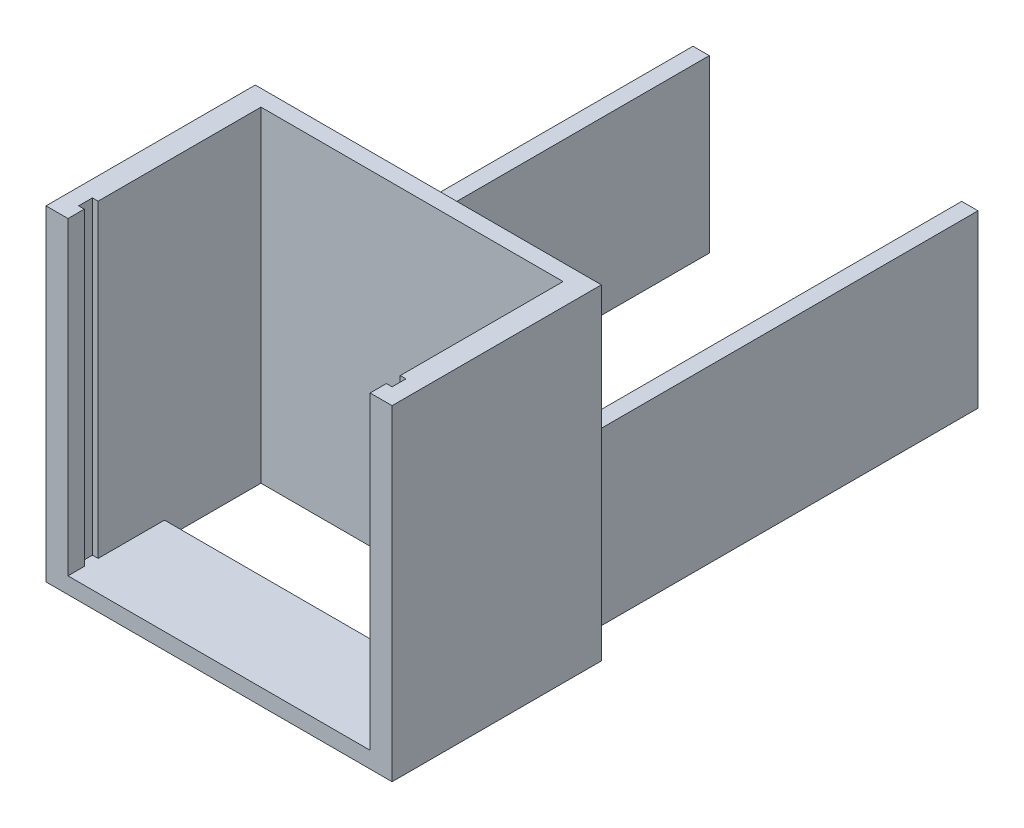
SolidWorks part; units mm, degrees
ref_plane "Front Plane" through (0, 0, 0) normal (0, 0, 1) x (1, 0, 0)
ref_plane "Top Plane" through (0, 0, 0) normal (0, 1, 0) x (1, 0, 0)
ref_plane "Right Plane" through (0, 0, 0) normal (1, 0, 0) x (0, 0, -1)
sketch "Sketch1" plane through (0, 0, 0) normal (0, 1, 0) x (1, 0, 0)
  line L5 (-62.899, -24.3935) -> (-24.399, -24.3935)
  line L6 (-62.899, -24.3935) -> (-62.899, -26.0935)
  line L7 (-62.899, -26.0935) -> (-24.399, -26.0935)
  line L8 (-24.399, -24.3935) -> (-24.399, -26.0935)
  line L9 (-62.199, -22.3935) -> (-25.099, -22.3935)
  line L10 (-62.199, -22.3935) -> (-62.199, -28.0935)
  line L11 (-62.199, -28.0935) -> (-25.099, -28.0935)
  line L12 (-25.099, -22.3935) -> (-25.099, -28.0935)
  line L13 (-64.899, -22.3935) -> (-22.399, -22.3935)
  line L14 (-64.899, -22.3935) -> (-64.899, -28.0935)
  line L15 (-64.899, -28.0935) -> (-22.399, -28.0935)
  line L16 (-22.399, -22.3935) -> (-22.399, -28.0935)
  point P8 (-24.399, -25.2435)
  dimension "D1" = 38.5
  dimension "D2" = 1.7
  dimension "D3" = 2
  dimension "D4" = 2
  dimension "D5" = 0.7
  dimension "D6" = 0.7
  dimension "D7" = 2
  dimension "D8" = 2
  dimension "D9" = 2
  dimension "D10" = 2
extrude "Boss-Extrude1" add sketch "Sketch1" along normal blind 38 contours L14 L15 L10 L7 L6 L5 L13 | L16 L13 L12 L5 L8 L7 L15
sketch "Sketch2" plane through (0, 0, 0) normal (0, 1, 0) x (1, 0, 0)
  line L1 (-64.899, -28.0935) -> (-22.399, -28.0935)
  line L2 (-64.899, -28.0935) -> (-64.899, -22.3935)
  line L3 (-64.899, -22.3935) -> (-22.399, -22.3935)
  line L4 (-22.399, -28.0935) -> (-22.399, -22.3935)
  dimension "D1" = 42.5
  dimension "D2" = 5.7
extrude "Boss-Extrude2" add sketch "Sketch2" against normal blind 2
sketch "Sketch3" plane through (0, 0, 22.3935) normal (0, 0, -1) x (-1, 0, 0)
  line L1 (22.399, 38) -> (64.899, 38)
  line L2 (22.399, 38) -> (22.399, -2)
  line L3 (22.399, -2) -> (64.899, -2)
  line L4 (64.899, 38) -> (64.899, -2)
  line L5 (25.099, 0) -> (62.199, 0)
  line L6 (25.099, 0) -> (25.099, 38)
  line L7 (25.099, 38) -> (62.199, 38)
  line L8 (62.199, 0) -> (62.199, 38)
  line M6 (62.199, 38) -> (62.199, 0)
  line M7 (62.199, 0) -> (25.099, 0)
  line M8 (25.099, 0) -> (25.099, 38)
  line M9 (25.099, 38) -> (22.399, 38)
  line M10 (22.399, 38) -> (22.399, -2)
  line M11 (22.399, -2) -> (64.899, -2)
  line M12 (64.899, -2) -> (64.899, 38)
  line M13 (64.899, 38) -> (62.199, 38)
  dimension "D1" = 42.5
  dimension "D2" = 40
  dimension "D3" = 38
  dimension "D4" = 37.1
extrude "Boss-Extrude3" add sketch "Sketch3" along normal blind 18 contours M13 M6 M7 M8 M9 M10 M11 M12
sketch "Sketch4" plane through (0, 0, 4.3935) normal (0, 0, -1) x (-1, 0, 0)
  line L1 (22.399, 38) -> (64.899, 38)
  line L2 (22.399, 38) -> (22.399, -2)
  line L3 (22.399, -2) -> (64.899, -2)
  line L4 (64.899, 38) -> (64.899, -2)
extrude "Boss-Extrude4" add sketch "Sketch4" along normal blind 2
sketch "Sketch5" plane through (0, 0, 0) normal (0, 1, 0) x (1, 0, 0)
  line L0 (-62.199, -16.2435) -> (-25.099, -16.2435)
  line L1 (-62.199, -4.3935) -> (-25.099, -4.3935)
  line L2 (-62.199, -4.3935) -> (-62.199, -28.0935)
  line L3 (-62.199, -28.0935) -> (-25.099, -28.0935)
  line L4 (-25.099, -4.3935) -> (-25.099, -28.0935)
  line M5 (-25.099, -24.3935) -> (-25.099, -4.3935)
  line M6 (-25.099, -4.3935) -> (-62.199, -4.3935)
  line M7 (-62.199, -4.3935) -> (-62.199, -24.3935)
  dimension "D1" = 37.1
  dimension "D2" = 23.7
  dimension "D3" = 11.85
extrude "Cut-Extrude1" cut sketch "Sketch5" against normal through all contours L0 M7 M5 M6
sketch "Sketch6" plane through (0, 0, 2.3935) normal (0, 0, -1) x (-1, 0, 0)
  line L1 (64.899, 38) -> (22.399, 38)
  line L2 (64.899, 38) -> (64.899, -2)
  line L3 (64.899, -2) -> (22.399, -2)
  line L4 (22.399, 38) -> (22.399, -2)
  line L17 (26.149, 19) -> (28.149, 19)
  line L18 (26.149, 19) -> (26.149, -2)
  line L19 (26.149, -2) -> (28.149, -2)
  line L20 (28.149, 19) -> (28.149, -2)
  line L21 (59.149, 19) -> (61.149, 19)
  line L22 (59.149, 19) -> (59.149, -2)
  line L23 (59.149, -2) -> (61.149, -2)
  line L24 (61.149, 19) -> (61.149, -2)
  dimension "D3" = 2
  dimension "D4" = 2
  dimension "D1" = 19
  dimension "D2" = 19
  dimension "D5" = 31
  dimension "D6" = 3.75
  dimension "D7" = 42.5
extrude "Boss-Extrude6" add sketch "Sketch6" along normal blind 50 contours L20 L17 L18 L3 | L24 L21 L22 L3
equation "\"camera side length\"= 38"
equation "\"camera module panel thickness\"= 1.7"
equation "\"tolerance\"= 0.5"
equation "\"D1@Sketch1\"=\"camera side length\"+\"tolerance\""
equation "\"D2@Sketch1\"=\"camera module panel thickness\""
equation "\"camera module side clearance\"= 0.7"
equation "\"camera mount thickness\"= 2"
equation "\"D3@Sketch1\"=\"camera mount thickness\""
equation "\"D4@Sketch1\"=\"camera mount thickness\""
equation "\"D5@Sketch1\"=\"camera module side clearance\""
equation "\"D6@Sketch1\"=\"camera module side clearance\""
equation "\"D7@Sketch1\"=\"camera mount thickness\""
equation "\"D8@Sketch1\"=\"camera mount thickness\""
equation "\"D9@Sketch1\"=\"camera mount thickness\""
equation "\"D10@Sketch1\"=\"camera mount thickness\""
equation "\"D1@Boss-Extrude1\"=\"camera side length\""
equation "\"D1@Boss-Extrude2\"=\"camera mount thickness\""
equation "\"camera module hole offset\"= 4.65"
equation "\"camera module hole diameter\"= 2.33"
equation "\"camera mount inner depth\"= 20"
equation "\"D1@Boss-Extrude3\"=\"camera mount inner depth\"-\"camera mount thickness\""
equation "\"D1@Boss-Extrude4\"=\"camera mount thickness\""
equation "\"light thickness\" =20"
equation "\"D1@Sketch6\"=\"camera side length\"/2"
equation "\"D2@Sketch6\"=\"D1@Sketch6\""
equation "\"D3@Sketch6\"=\"camera mount thickness\""
equation "\"D4@Sketch6\"= \"camera mount thickness\""
equation "\"D5@Sketch6\"=31"
equation "\"D6@Sketch6\"=(\"D7@Sketch6\"-(\"D5@Sketch6\"+2*\"D3@Sketch6\"))/2"
equation "\"D1@Boss-Extrude6\"=\"light thickness\"+30"
